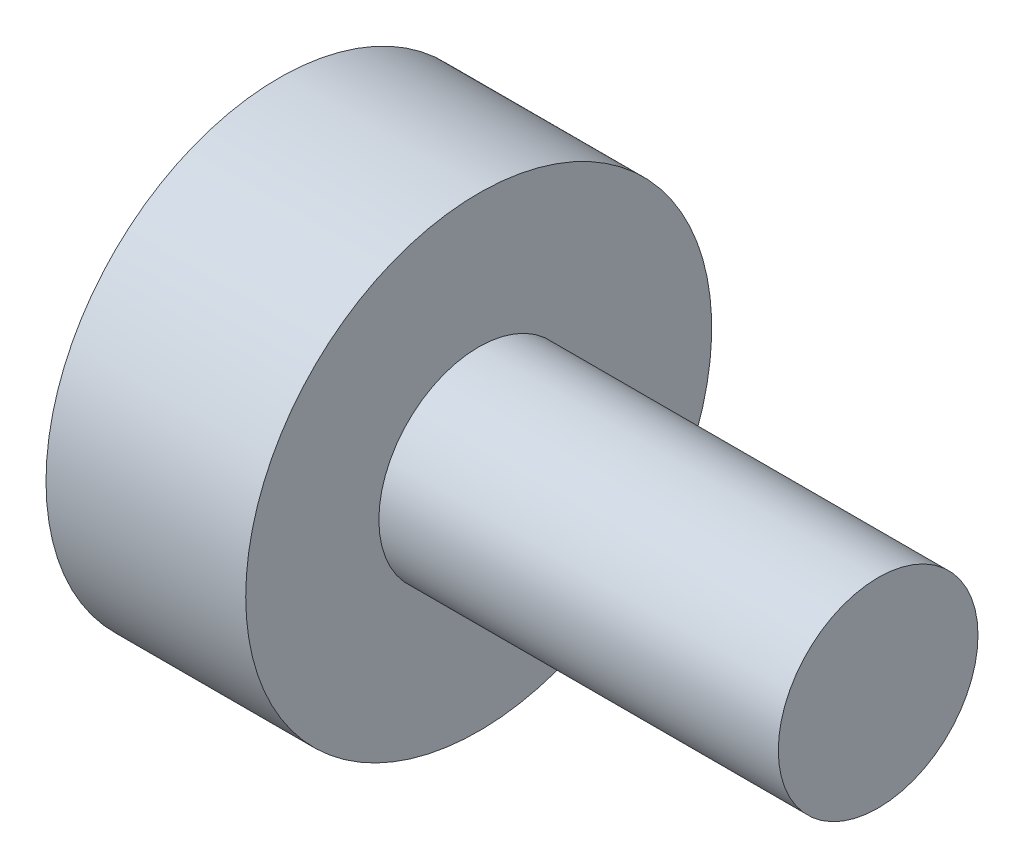
SolidWorks part; units mm, degrees
ref_plane "Спереди" through (0, 0, 0) normal (0, 0, 1) x (1, 0, 0)
ref_plane "Сверху" through (0, 0, 0) normal (0, 1, 0) x (1, 0, 0)
ref_plane "Справа" through (0, 0, 0) normal (1, 0, 0) x (0, 0, -1)
sketch "Эскиз1" plane through (0, 0, 0) normal (0, 0, 1) x (1, 0, 0)
  line L0 (0, 0) -> (100, 0)
  line L1 (0, 0) -> (0, 20)
  line L2 (0, 20) -> (10, 20)
  line L3 (10, 20) -> (10, 35)
  line L4 (10, 35) -> (40, 35)
  line L5 (40, 35) -> (40, 15)
  line L6 (40, 15) -> (100, 15)
  line L7 (100, 0) -> (100, 15)
revolve "Повернуть1" add sketch "Эскиз1" angle 360 about L0
ref_plane "Плоскость4" through (0, 0, 0) normal (1, 0, 0) x (0, 0, -1)
sketch "Эскиз2" plane through (0, 0, 0) normal (1, 0, 0) x (0, 0, -1)
  circle A0 centre (10, 0) radius 5
extrude "Вырез-Вытянуть1" cut sketch "Эскиз2" along normal blind 20
